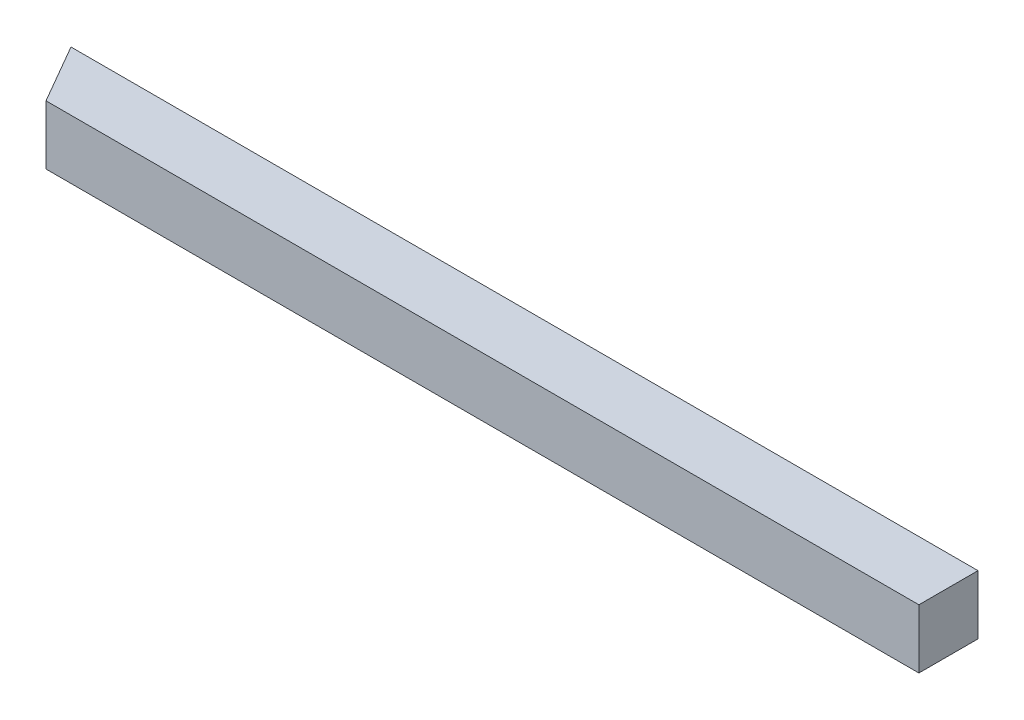
SolidWorks part; units mm, degrees
ref_plane "前视基准面" through (0, 0, 0) normal (0, 0, 1) x (1, 0, 0)
ref_plane "上视基准面" through (0, 0, 0) normal (0, 1, 0) x (1, 0, 0)
ref_plane "右视基准面" through (0, 0, 0) normal (1, 0, 0) x (0, 0, -1)
sketch "草图1" plane through (0, 0, 0) normal (0, 1, 0) x (1, 0, 0)
  line L0 (-600, -200) -> (600, -200) construction
  line L1 (270, -200) -> (360.1861, -356.2069) construction
  line L2 (293.094, -200) -> (600, -200)
  line L3 (600, -200) -> (600, -220)
  line L4 (293.094, -200) -> (304.641, -220)
  line L5 (304.641, -220) -> (600, -220)
  point P2 (0, -200)
  point P3 (-100, -200)
  point P5 (270, -200)
  point P8 (293.094, -200)
  point P9 (293.094, -200)
  dimension "D1" = 1200
  dimension "D2" = 200
  dimension "D3" = 500
  dimension "D4" = 370
  dimension "D5" = 60
  dimension "D6" = 20
  dimension "D7" = 20
extrude "凸台-拉伸1" add sketch "草图1" along normal blind 20 contours L5 L3 L2 L4
